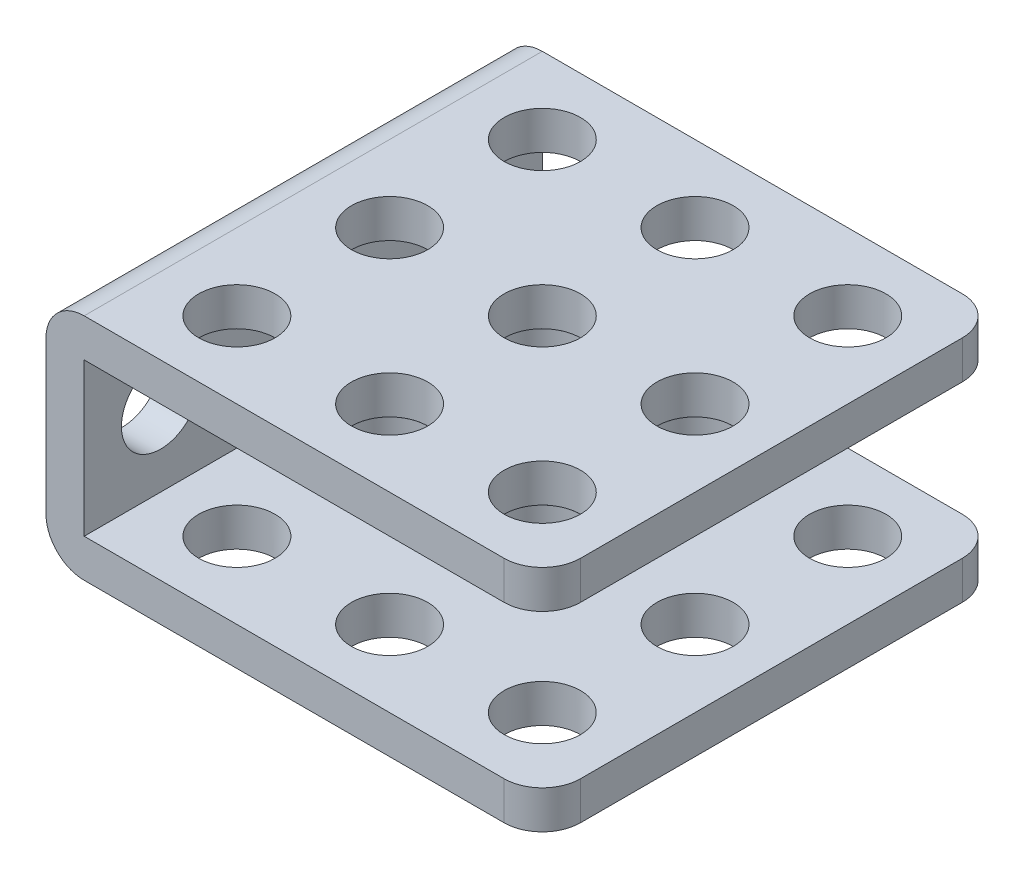
SolidWorks part; units mm, degrees
ref_plane "Front Plane" through (0, 0, 0) normal (0, 0, 1) x (1, 0, 0)
ref_plane "Top Plane" through (0, 0, 0) normal (0, 1, 0) x (1, 0, 0)
ref_plane "Right Plane" through (0, 0, 0) normal (1, 0, 0) x (0, 0, -1)
sketch "Sketch1" plane through (0, 0, 0) normal (0, 0, 1) x (1, 0, 0)
  line L0 (0, 0) -> (0, 10)
  line L2 (2, 10) -> (2, 2)
  line L3 (2, 2) -> (26, 2)
  line L4 (26, 2) -> (26, 0)
  line L5 (26, 0) -> (0, 0)
  line L7 (2, 10) -> (26, 10)
  line L8 (0, 10) -> (0, 12)
  line L9 (0, 12) -> (26, 12)
  line L10 (26, 10) -> (26, 12)
  dimension "D1" = 8
  dimension "D2" = 26
  dimension "D3" = 2
  dimension "D4" = 2
  dimension "D5" = 2
extrude "Boss-Extrude1" add sketch "Sketch1" along normal blind 24
sketch "Sketch2" plane through (2, 0, 0) normal (1, 0, 0) x (0, 0, -1)
  line L1 (-24, 2) -> (-24, 10) construction
  line L2 (-24, 10) -> (0, 10) construction
  circle A0 centre (-20, 6) radius 2.05
  dimension "D1" = 4.1
  dimension "D2" = 4
  dimension "D3" = 4
extrude "Cut-Extrude1" cut sketch "Sketch2" against normal through all
pattern_linear "LPattern1" count 3 spacing 8 along (0, 0, -1) of "Cut-Extrude1"
sketch "Sketch3" plane through (0, 2, 0) normal (0, 1, 0) x (1, 0, 0)
  line L0 (26, 0) -> (2, 0) construction
  line L1 (26, -24) -> (26, 0) construction
  circle A0 centre (22, -4) radius 2
  dimension "D1" = 4
  dimension "D2" = 4
  dimension "D3" = 4
extrude "Cut-Extrude2" cut sketch "Sketch3" against normal through all both and the other way through all
pattern_linear "LPattern2" count 3 spacing 8 along (0, 0, 1) count 3 spacing 8 along (-1, 0, 0) of "Cut-Extrude2"
fillet "Fillet1" radius 2 6 edges at (26, 1, 0) (26, 1, 24) (0, 0, 12) (0, 12, 12) (26, 11, 24) (26, 11, 0)
